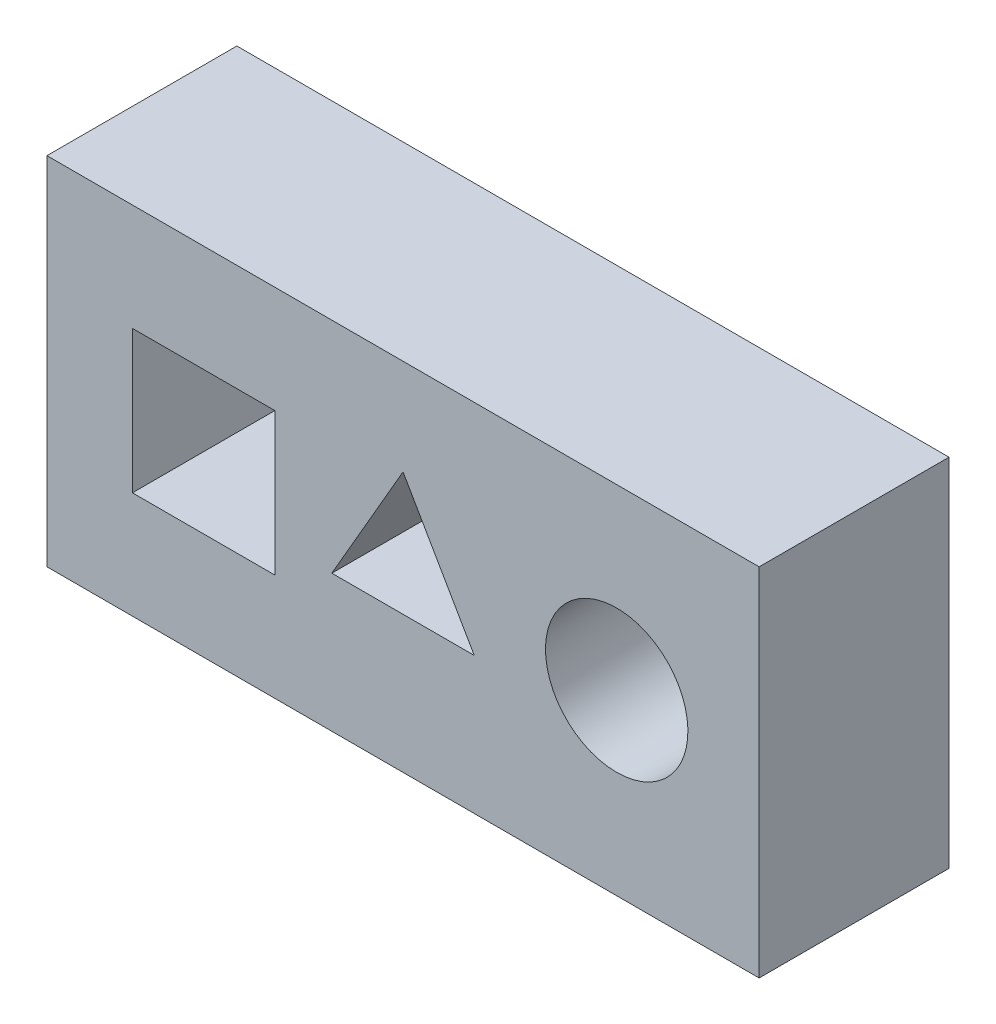
SolidWorks part; units mm, degrees
ref_plane "Front Plane" through (0, 0, 0) normal (0, 0, 1) x (1, 0, 0)
ref_plane "Top Plane" through (0, 0, 0) normal (0, 1, 0) x (1, 0, 0)
ref_plane "Right Plane" through (0, 0, 0) normal (1, 0, 0) x (0, 0, -1)
sketch "Sketch1" plane through (0, 0, 0) normal (0, 0, 1) x (1, 0, 0)
  line L1 (125, -62.5) -> (-125, -62.5)
  line L2 (125, -62.5) -> (125, 62.5)
  line L3 (125, 62.5) -> (-125, 62.5)
  line L4 (-125, -62.5) -> (-125, 62.5)
  line L5 (125, -62.5) -> (-125, 62.5) construction
  line L6 (125, 62.5) -> (-125, -62.5) construction
  line L7 (115, -57.5) -> (-115, -57.5)
  line L8 (115, -57.5) -> (115, 57.5)
  line L9 (115, 57.5) -> (-115, 57.5)
  line L10 (-115, -57.5) -> (-115, 57.5)
  line L11 (115, -57.5) -> (-115, 57.5) construction
  line L12 (115, 57.5) -> (-115, -57.5) construction
  point P0 (0, 0)
  point P6 (0, 0)
  dimension "D1" = 250
  dimension "D2" = 125
  dimension "D3" = 230
extrude "Boss-Extrude1" add sketch "Sketch1" along normal blind 100
sketch "Sketch2" plane through (0, 0, 0) normal (0, 0, -1) x (-1, 0, 0)
  line L1 (125, 62.5) -> (-125, 62.5)
  line L2 (125, 62.5) -> (125, -62.5)
  line L3 (125, -62.5) -> (-125, -62.5)
  line L4 (-125, 62.5) -> (-125, -62.5)
sketch "Sketch3" plane through (0, 0, 100) normal (0, 0, 1) x (1, 0, 0)
  line L0 (-125, 0) -> (125, 0) construction
  line L1 (-125, 62.5) -> (125, 62.5)
  line L2 (-125, 62.5) -> (-125, -62.5)
  line L3 (-125, -62.5) -> (125, -62.5)
  line L4 (125, 62.5) -> (125, -62.5)
  line L5 (0, 62.5) -> (0, -62.5) construction
  line L6 (-25, -14.4338) -> (0, 28.8675)
  line L7 (-95, 25) -> (-45, 25)
  line L8 (-95, 25) -> (-95, -25)
  line L9 (-95, -25) -> (-45, -25)
  line L10 (-45, 25) -> (-45, -25)
  line L11 (-95, 25) -> (-45, -25) construction
  line L12 (-95, -25) -> (-45, 25) construction
  line L14 (-1.3522, 0) -> (0, -1.3522)
  line L18 (0, 28.8675) -> (25, -14.4338)
  line L19 (25, -14.4338) -> (-25, -14.4338)
  line L20 (-25, -14.4338) -> (12.5, 7.2169) construction
  line L21 (25, -14.4338) -> (-12.5, 7.2169) construction
  line L22 (0, 28.8675) -> (0, 0) construction
  circle A0 centre (75, 0) radius 25
  point P10 (-70, 0)
  point P20 (0, 0)
  point P27 (7.7505, -5.3087)
  point P28 (0, 0)
  line M21 (-125, 62.5) -> (-125, -62.5)
  line M22 (-125, -62.5) -> (125, -62.5)
  line M23 (125, -62.5) -> (125, 62.5)
  line M24 (125, 62.5) -> (-125, 62.5)
  line M25 (115, -57.5) -> (-115, -57.5)
  line M26 (-115, -57.5) -> (-115, 57.5)
  line M27 (-115, 57.5) -> (115, 57.5)
  line M28 (115, 57.5) -> (115, -57.5)
  dimension "D2" = 50
  dimension "D3" = 50
  dimension "D1" = 30
  dimension "D4" = 50
  dimension "D5" = 50
  dimension "D6" = 50
  dimension "D7" = 50
  dimension "D8" = 50
extrude "Boss-Extrude4" add sketch "Sketch3" against normal up to surface (100 mm away) contours A0 L7 L10 L9 L8 L18 L19 L6 M25 M28 M27 M26 | M24 M21 M22 M23 M28 M25 M26 M27 up to face at (0, 0, 0)
scale "Scale2" scale about centroid uniform scaling no x scale factor 1.2 y scale factor 1.2 z scale factor 0.8
